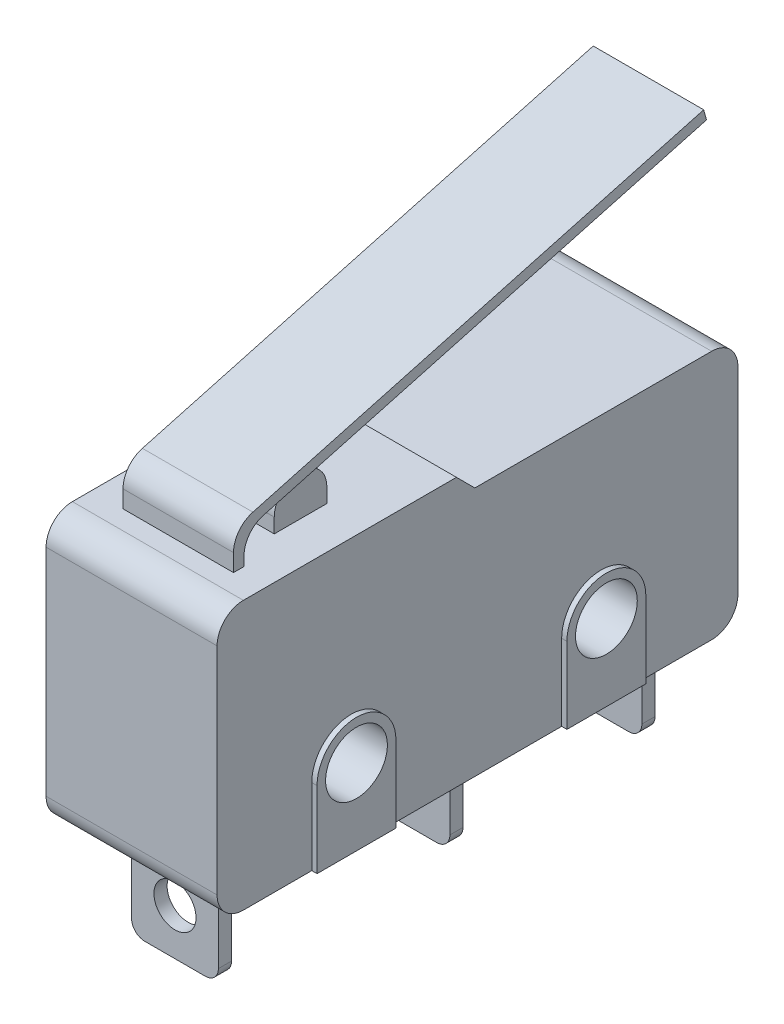
SolidWorks part; units mm, degrees
ref_plane "前视基准面" through (0, 0, 0) normal (0, 0, 1) x (1, 0, 0)
ref_plane "上视基准面" through (0, 0, 0) normal (0, 1, 0) x (1, 0, 0)
ref_plane "右视基准面" through (0, 0, 0) normal (1, 0, 0) x (0, 0, -1)
sketch "草图1" plane through (0, 0, 0) normal (1, 0, 0) x (0, 0, -1)
  line L1 (-9.9, 5.1) -> (9.9, 5.1)
  line L2 (-9.9, 5.1) -> (-9.9, -5.1)
  line L3 (-9.9, -5.1) -> (9.9, -5.1)
  line L4 (9.9, 5.1) -> (9.9, -5.1)
  line L5 (-9.9, 5.1) -> (9.9, -5.1) construction
  line L6 (-9.9, -5.1) -> (9.9, 5.1) construction
  point P0 (0, 0)
  dimension "D1" = 19.8
  dimension "D2" = 10.2
extrude "凸台-拉伸1" add sketch "草图1" along normal blind 3.2 and the other way blind 3.3
sketch "草图2" plane through (3.2, 0, 0) normal (1, 0, 0) x (0, 0, -1)
  line L0 (-0.8, 5.1) -> (-0.1, 4.4)
  line L1 (9.9, 5.1) -> (-9.9, 5.1) construction
  line L2 (-0.1, 4.4) -> (9.9, 4.4)
  line L3 (9.9, -5.1) -> (9.9, 5.1) construction
  line L4 (-0.8, 5.1) -> (9.9, 5.1)
  line L5 (9.9, 5.1) -> (9.9, 4.4)
  dimension "D1" = 0.7
  dimension "D2" = 10
  dimension "D3" = 135
extrude "切除-拉伸1" cut sketch "草图2" against normal through all
fillet "圆角1" radius 1 4 edges at (-0.05, -5.1, 9.9) (-0.05, -5.1, -9.9) (-0.05, 4.4, -9.9) (-0.05, 5.1, 9.9)
sketch "草图4" plane through (0, 0, 0) normal (1, 0, 0) x (0, 0, -1)
  line L0 (-8.9, -5.1) -> (8.9, -5.1) construction
  line L1 (-8.3, -5.1) -> (-7.8, -5.1)
  line L2 (-8.3, -5.1) -> (-8.3, -8.6)
  line L3 (-8.3, -8.6) -> (-7.8, -8.6)
  line L4 (-7.8, -5.1) -> (-7.8, -8.6)
  line L5 (-9.9, 4.1) -> (-9.9, -4.1) construction
  line L7 (7.8, -5.1) -> (7.8, -8.6)
  line L8 (8.3, -8.6) -> (7.8, -8.6)
  line L9 (8.3, -5.1) -> (8.3, -8.6)
  line L10 (8.3, -5.1) -> (7.8, -5.1)
  line L11 (-8.3, -5.1) -> (-7.8, -5.1)
  line L12 (0.5, -8.6) -> (1, -8.6)
  line L13 (0.5, -8.6) -> (0.5, -5.1)
  line L15 (1, -8.6) -> (1, -5.1)
  line L16 (0.5, -8.6) -> (1, -5.1) construction
  line L17 (0.5, -5.1) -> (1, -8.6) construction
  line L18 (7.8, -5.1) -> (8.3, -5.1)
  line L19 (0.5, -5.1) -> (1, -5.1)
  point P6 (0.75, -6.85)
  dimension "D1" = 0.5
  dimension "D2" = 0.5
  dimension "D3" = 0.5
  dimension "D4" = 3.5
  dimension "D5" = 3.5
  dimension "D6" = 1.6
  dimension "D7" = 8.8
  dimension "D8" = 7.3
extrude "凸台-拉伸2" add sketch "草图4" along normal blind 1.65 and the other way blind 1.65 contours L4 L1 L2 L3 | L19 L13 L12 L15 | L9 L10 L7 L8
fillet "圆角2" radius 0.5 6 edges at (-1.65, -8.6, 8.05) (1.65, -8.6, 8.05) (1.65, -8.6, -8.05) (-1.65, -8.6, -8.05) (1.65, -8.6, -0.75) (-1.65, -8.6, -0.75)
sketch "草图5" plane through (0, 0, 8.3) normal (0, 0, 1) x (1, 0, 0)
  line L0 (0, -5.1) -> (0, -8.6) construction
  line L1 (-1.65, -5.1) -> (1.65, -5.1) construction
  line L2 (-1.15, -8.6) -> (1.15, -8.6) construction
  circle A0 centre (0, -6.85) radius 0.8
  dimension "D1" = 1.6
extrude "切除-拉伸2" cut sketch "草图5" against normal through all
sketch "草图8" plane through (3.2, 0, 0) normal (1, 0, 0) x (0, 0, -1)
  line L0 (0, 0) -> (0, -10.3076) construction
  line L2 (-8.9, -5.1) -> (8.9, -5.1) construction
  line L3 (-9.9, 4.1) -> (-9.9, -4.1) construction
  circle A0 centre (-4.8, -2.2) radius 1.175
  circle A3 centre (4.7, -2.2) radius 1.175
  dimension "D1" = 2.35
  dimension "D2" = 2.9
  dimension "D3" = 5.1
  dimension "D4" = 2.35
  dimension "D5" = 2.9
  dimension "D6" = 9.5
extrude "切除-拉伸3" cut sketch "草图8" against normal through all
sketch "草图6" plane through (0, 0, 0) normal (1, 0, 0) x (0, 0, -1)
  line L2 (-7.7752, 6.2172) -> (9.8053, 11.0141)
  line L5 (-8.1752, 6.5227) -> (9.7, 11.4)
  line L7 (9.8053, 11.0141) -> (9.7, 11.4)
  line L8 (-8.1752, 4.7437) -> (-8.1752, 6.5227) construction
  line L10 (-7.7752, 4.7437) -> (-7.7752, 6.2172) construction
  line L11 (-7.7752, 6.2172) -> (-7.7752, 5.1)
  line L12 (-0.8, 5.1) -> (-8.9, 5.1) construction
  line L13 (-8.1752, 6.5227) -> (-8.1752, 5.1)
  line L14 (-8.1752, 5.1) -> (-7.7752, 5.1)
  circle A1 centre (-4.8, -2.2) radius 1.175 construction
  circle A2 centre (4.7, -2.2) radius 1.175 construction
  dimension "D1" = 13.6
  dimension "D2" = 0.4
  dimension "D4" = 14.5
  dimension "D3" = 0.4
extrude "凸台-拉伸3" add sketch "草图6" along normal blind 2.1 and the other way blind 2.1
sketch "草图7" plane through (0, 0, 0) normal (1, 0, 0) x (0, 0, -1)
  line L1 (-4.1267, 5.6532) -> (-4.1267, 5.1)
  line L2 (-0.8, 5.1) -> (-8.9, 5.1) construction
  line L3 (-6.1267, 5.6532) -> (-6.1267, 5.1)
  line L4 (-6.1267, 5.1) -> (-4.1267, 5.1)
  arc A0 (-4.1267, 5.6532) -> (-6.1267, 5.6532) centre (-5.1267, 5.6532) ccw
  dimension "D1" = 2
extrude "凸台-拉伸5" add sketch "草图7" along normal blind 1.6 and the other way blind 1.5
fillet "圆角3" radius 1 2 edges at (0, 6.5227, 8.1752) (0, 6.2172, 7.7752)
sketch "草图9" plane through (3.2, 0, 0) normal (1, 0, 0) x (0, 0, -1)
  line L0 (-3.3, -2.2) -> (-3.3, -5.1)
  line L1 (-8.9, -5.1) -> (8.9, -5.1) construction
  line L2 (-6.3, -2.2) -> (-6.3, -5.1)
  line L3 (-6.3, -5.1) -> (-3.3, -5.1)
  line L4 (3.2, -2.2) -> (3.2, -5.1)
  line L5 (6.2, -2.2) -> (6.2, -5.1)
  line L6 (6.2, -5.1) -> (3.2, -5.1)
  arc A0 (-3.3, -2.2) -> (-6.3, -2.2) centre (-4.8, -2.2) ccw
  arc A1 (6.2, -2.2) -> (3.2, -2.2) centre (4.7, -2.2) ccw
  circle A2 centre (-4.8, -2.2) radius 1.175 construction
  circle A3 centre (-4.8, -2.2) radius 1.175
  circle A4 centre (4.7, -2.2) radius 1.175 construction
  circle A5 centre (4.7, -2.2) radius 1.175
  dimension "D1" = 3
  dimension "D2" = 3
extrude "凸台-拉伸6" add sketch "草图9" along normal blind 0.2
mirror "镜向1" about plane through (0, 0, 0) normal (1, 0, 0) of "凸台-拉伸6"
